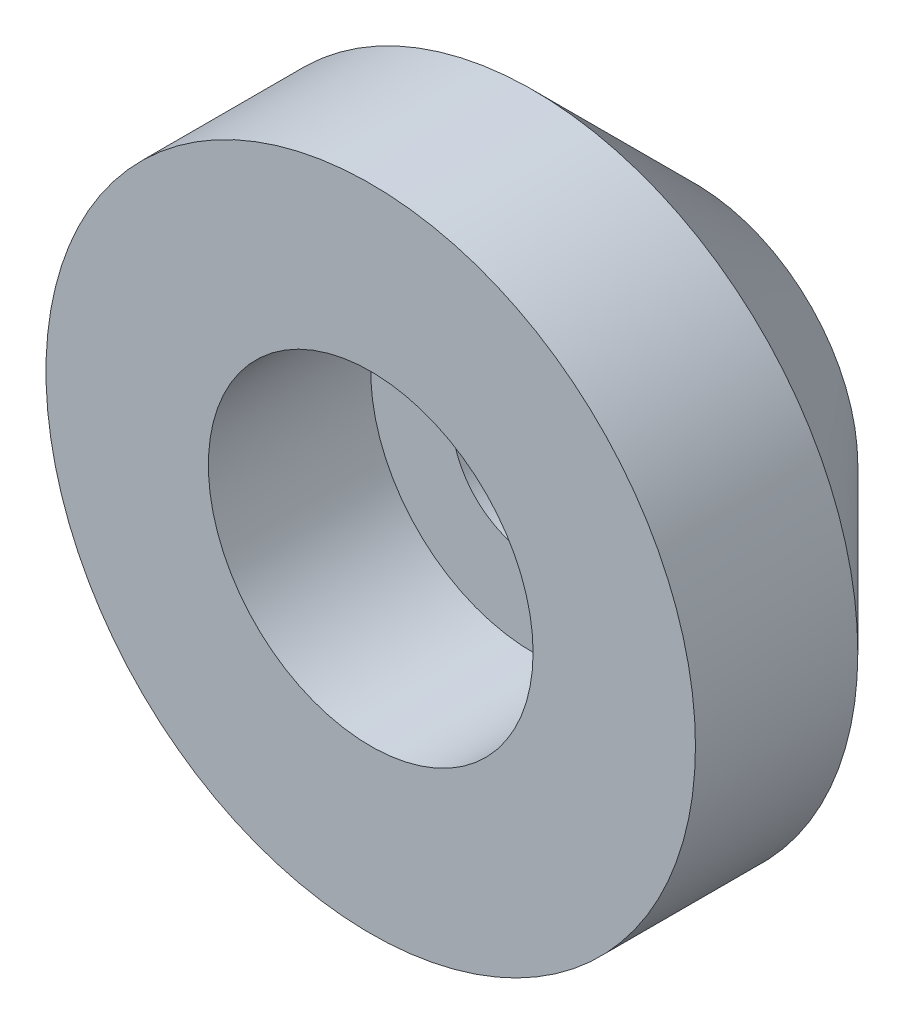
SolidWorks part; units mm, degrees
ref_plane "Front Plane" through (0, 0, 0) normal (0, 0, 1) x (1, 0, 0)
ref_plane "Top Plane" through (0, 0, 0) normal (0, 1, 0) x (1, 0, 0)
ref_plane "Right Plane" through (0, 0, 0) normal (1, 0, 0) x (0, 0, -1)
sketch "Sketch1" plane through (0, 0, 0) normal (0, 0, 1) x (1, 0, 0)
  circle A0 centre (0, 0) radius 5
  dimension "D1" = 10
extrude "Boss-Extrude1" add sketch "Sketch1" along normal blind 5
sketch "Sketch2" plane through (0, 0, 5) normal (0, 0, 1) x (1, 0, 0)
  circle A0 centre (0, 0) radius 2.5
  dimension "D1" = 5
extrude "Cut-Extrude1" cut sketch "Sketch2" against normal blind 2.5
sketch "Sketch3" plane through (0, 0, 0) normal (0, 0, -1) x (-1, 0, 0)
  circle A0 centre (0, 0) radius 1.25
  dimension "D1" = 2.5
extrude "Cut-Extrude2" cut sketch "Sketch3" against normal through all
chamfer "Chamfer1" distance 2.5 angle 45 1 edges at (5, 0, 0)
